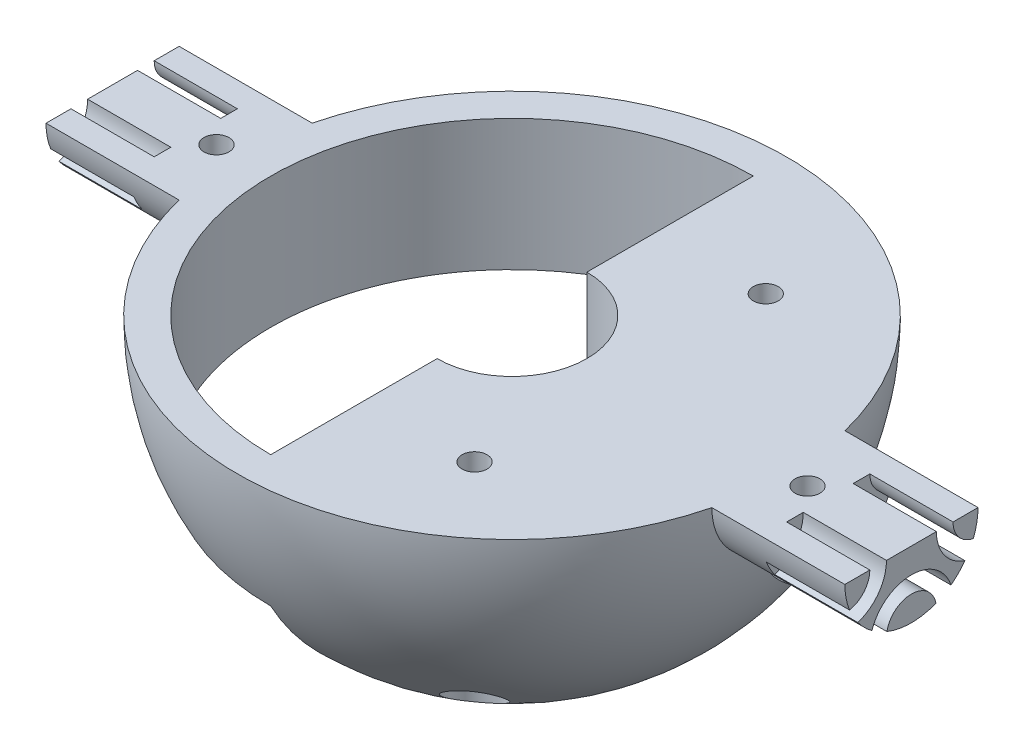
SolidWorks part; units mm, degrees
ref_plane "Plan de face" through (0, 0, 0) normal (0, 0, 1) x (1, 0, 0)
ref_plane "Plan de dessus" through (0, 0, 0) normal (0, 1, 0) x (1, 0, 0)
ref_plane "Plan de droite" through (0, 0, 0) normal (1, 0, 0) x (0, 0, -1)
sketch "Esquisse1" plane through (0, 0, 0) normal (0, 1, 0) x (1, 0, 0)
  line L0 (-33, 0) -> (33, 0) construction
  line L1 (-32.0156, -8) -> (-48, -8)
  line L2 (-48, -8) -> (-48, 0)
  line L3 (-48, 0) -> (-33, 0)
  line L4 (33, 0) -> (-33, 0)
  line L5 (0, 0) -> (0, -33) construction
  line L6 (48, -8) -> (48, 0)
  line L7 (48, 0) -> (33, 0)
  line L8 (32.0156, -8) -> (48, -8)
  arc A0 (-33, 0) -> (33, 0) centre (0, 0) ccw construction
  arc A1 (-30, 0) -> (30, 0) centre (0, 0) ccw construction
  arc A2 (-32.0156, -8) -> (33, 0) centre (0, 0) ccw
  point P3 (0, 0)
  dimension "D1" = 30
  dimension "D2" = 3
  dimension "D3" = 15
  dimension "D4" = 8
revolve "Révolution1" add sketch "Esquisse1" angle 90 about L0
sketch "Esquisse2" plane through (0, 0, 0) normal (0, 1, 0) x (1, 0, 0)
  line L0 (48, 0) -> (-48, 0) construction
  line L2 (0, -9) -> (0, -29)
  line L3 (9, 0) -> (29, 0)
  line L4 (9, 0) -> (-29, 0)
  arc A0 (-29, 0) -> (29, 0) centre (0, 0) ccw
  arc A1 (9, 0) -> (0, -9) centre (0, 0) cw
  dimension "D1" = 29
  dimension "D2" = 9
extrude "Enlèv. mat.-Extru.1" cut sketch "Esquisse2" against normal through all contours A1 L4 A0 L2
sketch "Esquisse3" plane through (0, 0, 0) normal (-1, 0, 0) x (0, 0, 1)
  line L0 (19, 0) -> (19, -15.8745) construction
  line L1 (9, 0) -> (29, 0) construction
  line L2 (19, -15.8745) -> (9, -15.8745) construction
  line L3 (9, -31.749) -> (9, 0) construction
  circle A0 centre (19, -15.8745) radius 1.5
  dimension "D1" = 3
extrude "Enlèv. mat.-Extru.2" cut sketch "Esquisse3" against normal blind 5
sketch "Esquisse4" plane through (-48, 0, 0) normal (-1, 0, 0) x (0, 0, 1)
  line L0 (8, 0) -> (0, 0) construction
  line L1 (0, 0) -> (5.6569, -5.6569) construction
  line L2 (5, 0) -> (3, 0)
  line L3 (0, -5) -> (0, -3)
  arc A0 (7.4375, -2.9468) -> (5, 0) centre (8, 0) cw
  arc A1 (0, -8) -> (8, 0) centre (0, 0) ccw construction
  arc A2 (6.4375, -4.7496) -> (3, 0) centre (8, 0) cw
  arc A3 (6.4375, -4.7496) -> (7.4375, -2.9468) centre (0, 0) ccw
  arc A4 (2.9468, -7.4375) -> (0, -5) centre (0, -8) ccw
  arc A5 (4.7496, -6.4375) -> (2.9468, -7.4375) centre (0, 0) cw
  arc A6 (4.7496, -6.4375) -> (0, -3) centre (0, -8) ccw
  dimension "D1" = 2
  dimension "D2" = 3
extrude "Enlèv. mat.-Extru.3" cut sketch "Esquisse4" against normal blind 10
mirror "Symétrie1" about plane through (0, 0, 0) normal (1, 0, 0) of "Enlèv. mat.-Extru.3"
mirror "Symétrie2"
ref_plane "Plan1" through (0, -8, 0) normal (0, -1, 0) x (-1, 0, 0)
sketch "Esquisse5" plane through (0, -8, 0) normal (0, -1, 0) x (-1, 0, 0)
  line L0 (32.0156, 8) -> (32.0156, -8) construction
  circle A0 centre (35.5156, 0) radius 3.5
  dimension "D1" = 7
extrude "Boss.-Extru.1" add sketch "Esquisse5" against normal blind 5
sketch "Esquisse6" plane through (0, -8, 0) normal (0, -1, 0) x (1, 0, 0)
  circle A0 centre (-35.5156, 0) radius 1.5
  arc A1 (-39.0156, 0) -> (-32.0156, 0) centre (-35.5156, 0) ccw construction
  dimension "D1" = 3
extrude "Enlèv. mat.-Extru.4" cut sketch "Esquisse6" against normal through all
sketch "Esquisse7" plane through (0, -8, 0) normal (0, -1, 0) x (1, 0, 0)
  circle A0 centre (-35.5156, 0) radius 2.5
  dimension "D1" = 5
extrude "Enlèv. mat.-Extru.5" cut sketch "Esquisse7" against normal blind 3
mirror "Symétrie3" about plane through (0, 0, 0) normal (1, 0, 0) of "Enlèv. mat.-Extru.5", "Enlèv. mat.-Extru.4", "Boss.-Extru.1"
ref_plane "Plan2" through (0, -18, 0) normal (0, 1, 0) x (1, 0, 0)
sketch "Esquisse8" plane through (0, -18, 0) normal (0, 1, 0) x (1, 0, 0)
  line L0 (13, -17.5) -> (13, 17.5) construction
  line L1 (0, 0) -> (13, 0) construction
  circle A0 centre (13, 17.5) radius 3
  circle A1 centre (13, -17.5) radius 3
  dimension "D1" = 6
  dimension "D2" = 35
  dimension "D3" = 13
extrude "Enlèv. mat.-Extru.6" cut sketch "Esquisse8" against normal through all
sketch "Esquisse9" plane through (0, -18, 0) normal (0, -1, 0) x (1, 0, 0)
  circle A0 centre (13, -17.5) radius 1.5
  circle A1 centre (13, 17.5) radius 1.5
  dimension "D1" = 3
extrude "Enlèv. mat.-Extru.7" cut sketch "Esquisse9" against normal through all
